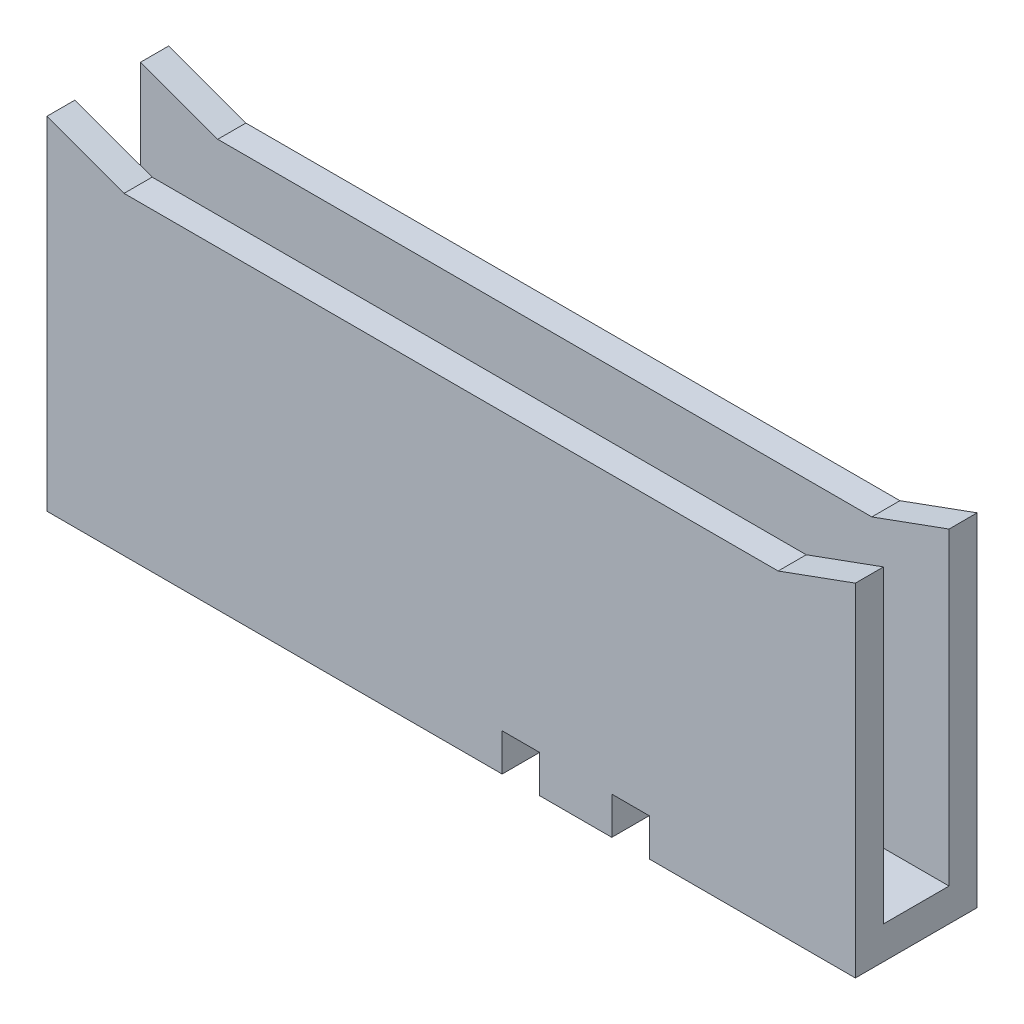
SolidWorks part; units mm, degrees
material "ABS"
ref_plane "正面" through (0, 0, 0) normal (0, 0, 1) x (1, 0, 0)
ref_plane "平面" through (0, 0, 0) normal (0, 1, 0) x (1, 0, 0)
ref_plane "右側面" through (0, 0, 0) normal (1, 0, 0) x (0, 0, -1)
sketch "ｽｹｯﾁ1" plane through (0, 0, 0) normal (0, 0, 1) x (1, 0, 0)
  line L1 (43.15, -16.75) -> (-43.15, -16.75)
  line L2 (43.15, -16.75) -> (43.15, 16.75)
  line L3 (43.15, 16.75) -> (-43.15, 16.75)
  line L4 (-43.15, -16.75) -> (-43.15, 16.75)
  line L5 (43.15, -16.75) -> (-43.15, 16.75) construction
  line L6 (43.15, 16.75) -> (-43.15, -16.75) construction
  point P0 (0, 0)
  dimension "D1" = 33.5
  dimension "D2" = 86.3
extrude "ﾎﾞｽ - 押し出し1" add sketch "ｽｹｯﾁ1" along normal blind 13
sketch "ｽｹｯﾁ3" plane through (0, 0, 0) normal (0, 0, -1) x (-1, 0, 0)
  line L0 (-43.15, 16.75) -> (-43.15, 19.75)
  line L1 (-43.15, 16.75) -> (-34.9076, 16.75)
  line L2 (-43.15, 16.75) -> (43.15, 16.75) construction
  line L3 (-34.9076, 16.75) -> (-43.15, 19.75)
  line L4 (43.15, 16.75) -> (43.15, 19.75)
  line L5 (43.15, 19.75) -> (34.9076, 16.75)
  line L6 (34.9076, 16.75) -> (43.15, 16.75)
  line L7 (-34.9076, 16.75) -> (-5.4, 6.0101) construction
  line L8 (34.9076, 16.75) -> (5.4, 6.0101) construction
  line L10 (43.15, -16.75) -> (-43.15, -16.75) construction
  dimension "D1" = 36.5
  dimension "D2" = 36.5
  dimension "D3" = 70
  dimension "D4" = 70
  dimension "D5" = 5.4
  dimension "D6" = 5.4
extrude "ﾎﾞｽ - 押し出し2" add sketch "ｽｹｯﾁ3" against normal blind 13
sketch "ｽｹｯﾁ6" plane through (0, 0, 0) normal (0, 0, -1) x (-1, 0, 0)
  line L0 (-40.15, 15.4656) -> (-40.15, -13.75)
  line L1 (-40.15, -13.75) -> (-8.4, -13.75)
  line L2 (-8.4, -13.75) -> (-8.4, 3.9095)
  line L3 (-8.4, 3.9095) -> (-40.15, 15.4656)
  line L4 (8.4, -13.75) -> (40.15, -13.75)
  line L5 (40.15, -13.75) -> (40.15, 15.4656)
  line L6 (40.15, 15.4656) -> (8.4, 3.9095)
  line L7 (8.4, -13.75) -> (8.4, 3.9095)
  line L8 (-34.9076, 16.75) -> (-43.15, 19.75) construction
  line L9 (43.15, 19.75) -> (34.9076, 16.75) construction
  line L10 (-43.15, -16.75) -> (-43.15, 19.75) construction
  line L11 (43.15, -16.75) -> (-43.15, -16.75) construction
  line L12 (43.15, 19.75) -> (43.15, -16.75) construction
  line L13 (-34.9076, 16.75) -> (34.9076, 16.75) construction
  line L14 (5.4, -13.75) -> (-5.4, -13.75)
  line L15 (5.4, -13.75) -> (5.4, 13.75)
  line L16 (5.4, 13.75) -> (-5.4, 13.75)
  line L17 (-5.4, -13.75) -> (-5.4, 13.75)
  line L18 (5.4, -13.75) -> (-5.4, 13.75) construction
  line L19 (5.4, 13.75) -> (-5.4, -13.75) construction
  line L20 (-26.6651, 13.75) -> (-8.4, 13.75)
  line L21 (-8.4, 13.75) -> (-8.4, 7.102)
  line L22 (-8.4, 7.102) -> (-26.6651, 13.75)
  line L23 (8.4, 13.75) -> (8.4, 7.102)
  line L24 (8.4, 7.102) -> (26.6651, 13.75)
  line L25 (26.6651, 13.75) -> (8.4, 13.75)
  point P18 (39.0288, 18.25)
  point P19 (0, 0)
  dimension "D1" = 3
  dimension "D2" = 3
  dimension "D3" = 3
  dimension "D4" = 3
  dimension "D5" = 3
  dimension "D6" = 3
  dimension "D7" = 3
  dimension "D8" = 10.8
  dimension "D9" = 3
  dimension "D10" = 3
  dimension "D11" = 3
extrude "ｶｯﾄ - 押し出し1" [suppressed] cut sketch "ｽｹｯﾁ6" against normal through all
sketch "ｽｹｯﾁ7" plane through (0, 16.75, 0) normal (0, 1, 0) x (1, 0, 0)
  line L0 (0, 0) -> (0, -13) construction
  line L1 (34.9076, 0) -> (-34.9076, 0) construction
  line L2 (34.9076, -13) -> (-34.9076, -13) construction
  line L4 (-43.15, -10) -> (43.15, -10)
  line L5 (-43.15, -10) -> (-43.15, -3)
  line L6 (-43.15, -3) -> (43.15, -3)
  line L7 (43.15, -10) -> (43.15, -3)
  line L8 (-43.15, -10) -> (43.15, -3) construction
  line L9 (-43.15, -3) -> (43.15, -10) construction
  point P6 (0, -6.5)
  dimension "D1" = 86.3
  dimension "D2" = 7
extrude "ｶｯﾄ - 押し出し3" cut sketch "ｽｹｯﾁ7" along normal up to next
sketch "ｽｹｯﾁ8" plane through (0, 16.75, 0) normal (0, 1, 0) x (1, 0, 0)
  line L0 (0, 0) -> (0, -13) construction
  line L1 (34.9076, 0) -> (-34.9076, 0) construction
  line L2 (34.9076, -13) -> (-34.9076, -13) construction
  line L4 (43.15, -10) -> (-43.15, -10)
  line L5 (43.15, -10) -> (43.15, -3)
  line L6 (43.15, -3) -> (-43.15, -3)
  line L7 (-43.15, -10) -> (-43.15, -3)
  line L8 (43.15, -10) -> (-43.15, -3) construction
  line L9 (43.15, -3) -> (-43.15, -10) construction
  point P6 (0, -6.5)
extrude "ｶｯﾄ - 押し出し4" cut sketch "ｽｹｯﾁ8" against normal blind 30
sketch "ｽｹｯﾁ9" plane through (0, -16.75, 0) normal (0, -1, 0) x (1, 0, 0)
  line L0 (43.15, 6.5) -> (-43.15, 6.5) construction
  line L1 (43.15, 13) -> (43.15, 0) construction
  line L2 (-43.15, 13) -> (-43.15, 0) construction
  circle A0 centre (-38.15, 6.5) radius 0.975
  circle A1 centre (38.15, 6.5) radius 0.975
  dimension "D1" = 5
  dimension "D2" = 5
  dimension "D3" = 1.95
extrude "ｶｯﾄ - 押し出し5" cut sketch "ｽｹｯﾁ9" against normal through all
sketch "ｽｹｯﾁ10" plane through (0, 0, 13) normal (0, 0, 1) x (1, 0, 0)
  line L0 (-43.15, -16.75) -> (43.15, -16.75) construction
  line L1 (5.45, -12.75) -> (9.45, -12.75)
  line L2 (5.45, -12.75) -> (5.45, -16.75)
  line L3 (5.45, -16.75) -> (9.45, -16.75)
  line L4 (9.45, -12.75) -> (9.45, -16.75)
  line L5 (5.45, -12.75) -> (9.45, -16.75) construction
  line L6 (5.45, -16.75) -> (9.45, -12.75) construction
  line L8 (43.15, -16.75) -> (43.15, 19.75) construction
  line L10 (21.15, -12.75) -> (17.15, -12.75)
  line L11 (21.15, -12.75) -> (21.15, -16.75)
  line L12 (21.15, -16.75) -> (17.15, -16.75)
  line L13 (17.15, -12.75) -> (17.15, -16.75)
  line L14 (21.15, -12.75) -> (17.15, -16.75) construction
  line L15 (21.15, -16.75) -> (17.15, -12.75) construction
  point P0 (7.45, -14.75)
  point P9 (19.15, -14.75)
  dimension "D1" = 4
  dimension "D2" = 4
  dimension "D3" = 37.7
  dimension "D4" = 7.7
extrude "ｶｯﾄ - 押し出し6" cut sketch "ｽｹｯﾁ10" against normal through all
